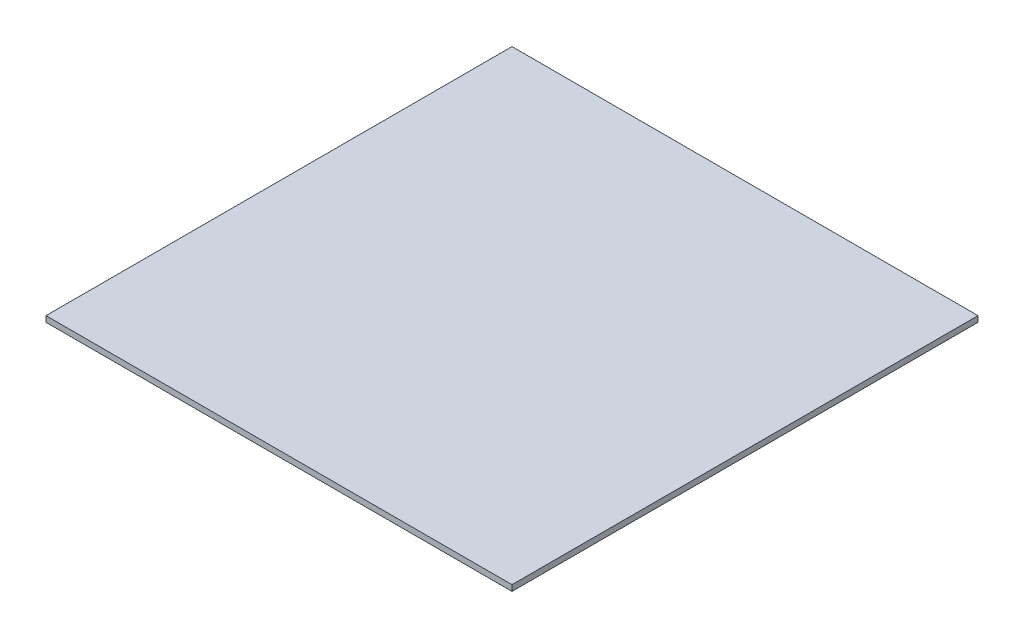
SolidWorks part; units mm, degrees
material "Thornel VCB-20 Carbon Cloth"
ref_plane "Спереди" through (0, 0, 0) normal (0, 0, 1) x (1, 0, 0)
ref_plane "Сверху" through (0, 0, 0) normal (0, 1, 0) x (1, 0, 0)
ref_plane "Справа" through (0, 0, 0) normal (1, 0, 0) x (0, 0, -1)
sketch "Sketch1" plane through (0, 0, 0) normal (0, 1, 0) x (1, 0, 0)
  line L1 (0, 0) -> (120, 0)
  line L2 (0, 0) -> (0, 120)
  line L3 (0, 120) -> (120, 120)
  line L4 (120, 0) -> (120, 120)
  dimension "D1" = 120
  dimension "D2" = 120
extrude "Boss-Extrude1" add sketch "Sketch1" along normal blind 1.5
